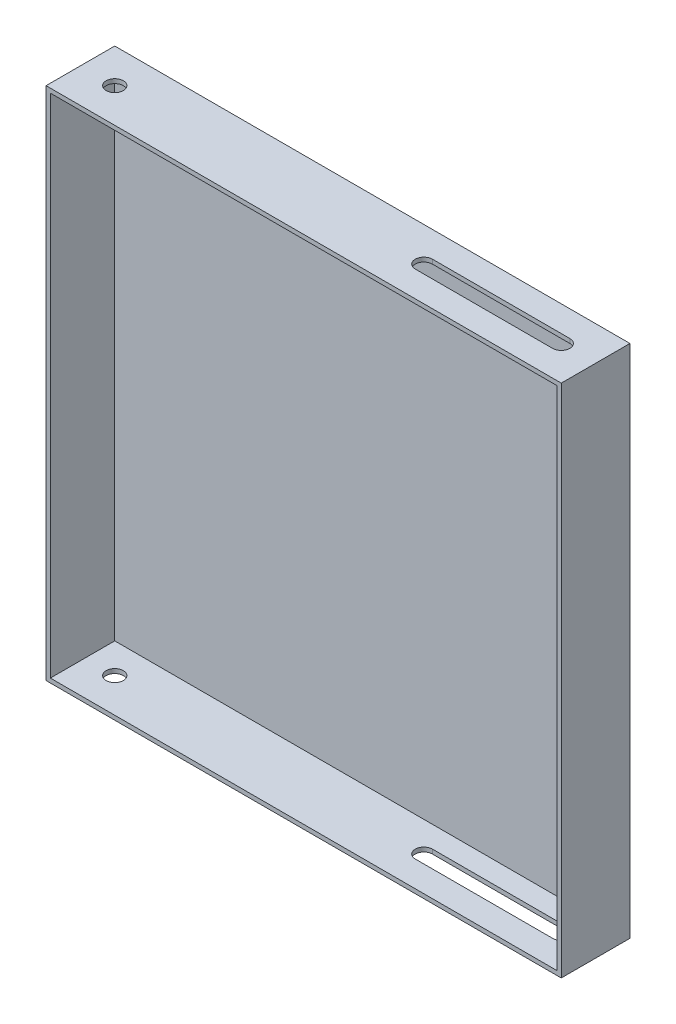
SolidWorks part; units mm, degrees
ref_plane "Front Plane" through (0, 0, 0) normal (0, 0, 1) x (1, 0, 0)
ref_plane "Top Plane" through (0, 0, 0) normal (0, 1, 0) x (1, 0, 0)
ref_plane "Right Plane" through (0, 0, 0) normal (1, 0, 0) x (0, 0, -1)
sketch "Sketch1" plane through (0, 0, 0) normal (0, 0, 1) x (1, 0, 0)
  line L1 (0, 0) -> (381, 0)
  line L2 (0, 0) -> (0, 381)
  line L3 (0, 381) -> (381, 381)
  line L4 (381, 0) -> (381, 381)
  dimension "D1" = 381
  dimension "D2" = 381
extrude "Boss-Extrude1" add sketch "Sketch1" along normal blind 50.8
shell "Shell1" thickness 3.175
sketch "Sketch2" plane through (0, 381, 0) normal (0, 1, 0) x (1, 0, 0)
  line L3 (0, -25.4) -> (25.4, -25.4) construction
  line L4 (0, -50.8) -> (0, 0) construction
  circle A0 centre (25.4, -25.4) radius 6.35
extrude "Cut-Extrude1" cut sketch "Sketch2" against normal blind 417.576
sketch "Sketch4" plane through (0, 381, 0) normal (0, 1, 0) x (1, 0, 0)
  line L2 (355.6, -31.75) -> (254, -31.75)
  line L3 (355.6, -19.05) -> (254, -19.05)
  circle A0 centre (355.6, -25.4) radius 6.35
  circle A1 centre (254, -25.4) radius 6.35
extrude "Cut-Extrude2" cut sketch "Sketch4" against normal blind 417.576 contours A1 | A1 L2 A0 L3 | A0
